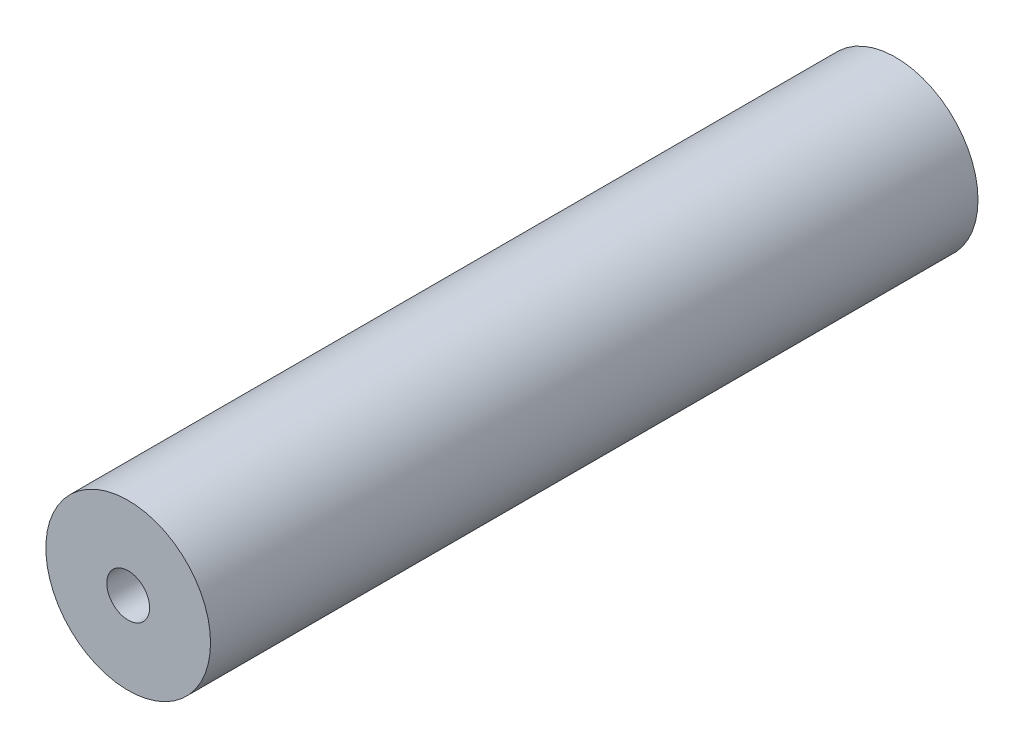
SolidWorks part; units mm, degrees
material "1060 合金"
ref_plane "正面" through (0, 0, 0) normal (0, 0, 1) x (1, 0, 0)
ref_plane "平面" through (0, 0, 0) normal (0, 1, 0) x (1, 0, 0)
ref_plane "右側面" through (0, 0, 0) normal (1, 0, 0) x (0, 0, -1)
sketch "ｽｹｯﾁ1" plane through (0, 0, 0) normal (0, 0, 1) x (1, 0, 0)
  circle A0 centre (0, 0) radius 5
  point P0 (0, 0)
  dimension "D1" = 10
extrude "ﾎﾞｽ - 押し出し1" add sketch "ｽｹｯﾁ1" along normal blind 46.6
sketch "ｽｹｯﾁ2" plane through (0, 0, 46.6) normal (0, 0, 1) x (1, 0, 0)
  circle A0 centre (0, 0) radius 1.3
  dimension "D1" = 2.6
extrude "ｶｯﾄ - 押し出し1" cut sketch "ｽｹｯﾁ2" against normal through all
